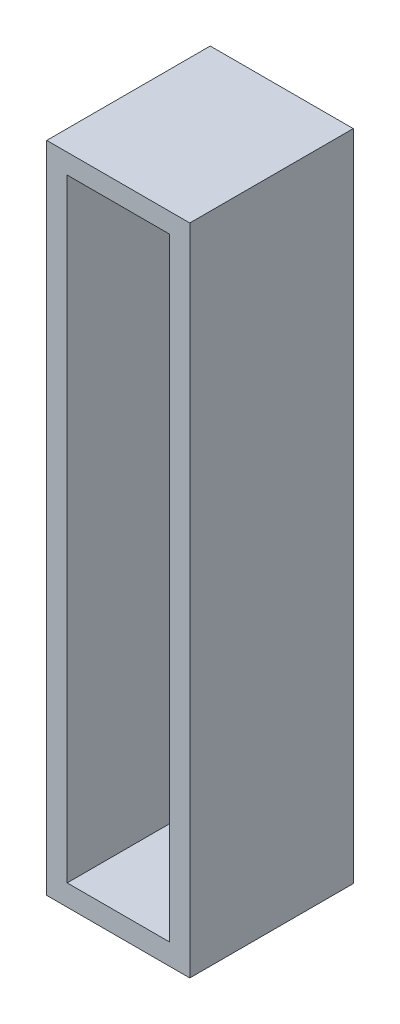
SolidWorks part; units mm, degrees
ref_plane "Front Plane" through (0, 0, 0) normal (0, 0, 1) x (1, 0, 0)
ref_plane "Top Plane" through (0, 0, 0) normal (0, 1, 0) x (1, 0, 0)
ref_plane "Right Plane" through (0, 0, 0) normal (1, 0, 0) x (0, 0, -1)
sketch "Sketch4" plane through (0, 0, 0) normal (0, 0, 1) x (1, 0, 0)
  line L0 (-2.9964, 21.7091) -> (-2.9964, -18.9309)
  line L1 (-2.9964, -18.9309) -> (5.8936, -18.9309)
  line L2 (5.8936, -18.9309) -> (5.8936, 21.7091)
  line L3 (5.8936, 21.7091) -> (-2.9964, 21.7091)
  line L4 (-1.7264, 20.4787) -> (-1.7264, -17.6213)
  line L5 (-1.7264, -17.6213) -> (4.6236, -17.6213)
  line L6 (4.6236, -17.6213) -> (4.6236, 20.4787)
  line L7 (4.6236, 20.4787) -> (-1.7264, 20.4787)
  dimension "D1" = 38.1
  dimension "D2" = 40.64
  dimension "D3" = 8.89
  dimension "D4" = 6.35
  dimension "D5" = 1.27
  dimension "D6" = 1.3097
extrude "Boss-Extrude2" add sketch "Sketch4" along normal blind 10.16
